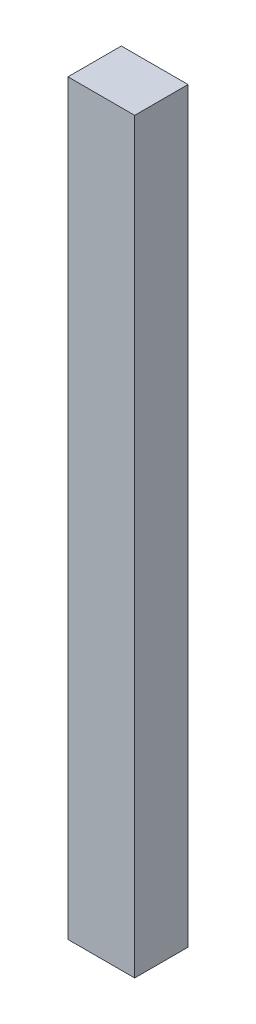
SolidWorks part; units mm, degrees
ref_plane "Front Plane" through (0, 0, 0) normal (0, 0, 1) x (1, 0, 0)
ref_plane "Top Plane" through (0, 0, 0) normal (0, 1, 0) x (1, 0, 0)
ref_plane "Right Plane" through (0, 0, 0) normal (1, 0, 0) x (0, 0, -1)
other "Configuration Table"
sketch "Sketch1" plane through (0, 0, 0) normal (0, 1, 0) x (1, 0, 0)
  line L0 (0, -40) -> (0, -20)
  line L1 (0, -20) -> (25, -20)
  line L2 (25, -20) -> (25, -40)
  line L3 (25, -40) -> (0, -40)
extrude "FKAP_cerceve_sol_1" add sketch "Sketch1" along normal blind 280 separate body
